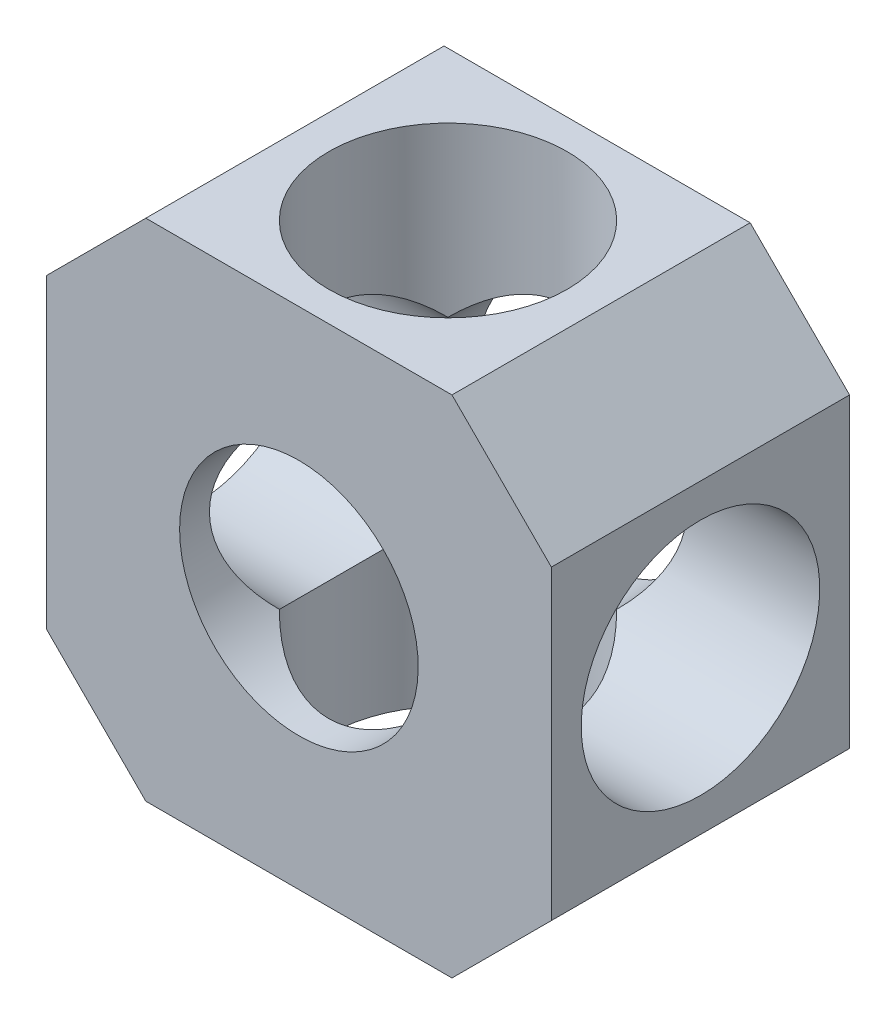
SolidWorks part; units mm, degrees
material "Malleable Cast Iron"
ref_plane "Front Plane" through (0, 0, 0) normal (0, 0, 1) x (1, 0, 0)
ref_plane "Top Plane" through (0, 0, 0) normal (0, 1, 0) x (1, 0, 0)
ref_plane "Right Plane" through (0, 0, 0) normal (1, 0, 0) x (0, 0, -1)
sketch "Sketch1" plane through (0, 0, 0) normal (0, 0, 1) x (1, 0, 0)
  line L1 (12.7, 12.7) -> (-12.7, 12.7)
  line L2 (12.7, 12.7) -> (12.7, -12.7)
  line L3 (12.7, -12.7) -> (-12.7, -12.7)
  line L4 (-12.7, 12.7) -> (-12.7, -12.7)
  line L5 (12.7, 12.7) -> (-12.7, -12.7) construction
  line L6 (12.7, -12.7) -> (-12.7, 12.7) construction
  point P0 (0, 0)
  dimension "D1" = 25.4
  dimension "D2" = 25.4
extrude "Boss-Extrude1" add sketch "Sketch1" along normal mid plane 15
chamfer "Chamfer1" distance 5 distance2 5 4 edges at (-12.7, -12.7, 0) (12.7, -12.7, 0) (-12.7, 12.7, 0) (12.7, 12.7, 0)
sketch "Sketch2" plane through (0, 0, 7.5) normal (0, 0, 1) x (1, 0, 0)
  circle A0 centre (0, 0) radius 6
extrude "Cut-Extrude1" cut sketch "Sketch2" against normal through all both and the other way through all
sketch "Sketch3" plane through (-12.7, 0, 0) normal (-1, 0, 0) x (0, 0, 1)
  circle A0 centre (0, 0) radius 6
extrude "Cut-Extrude2" cut sketch "Sketch3" against normal through all both and the other way through all
pattern_circular "CirPattern1" count 4 over 360 about axis through (0, 0, -7.5) along (0, 0, 1) of "Cut-Extrude2"
